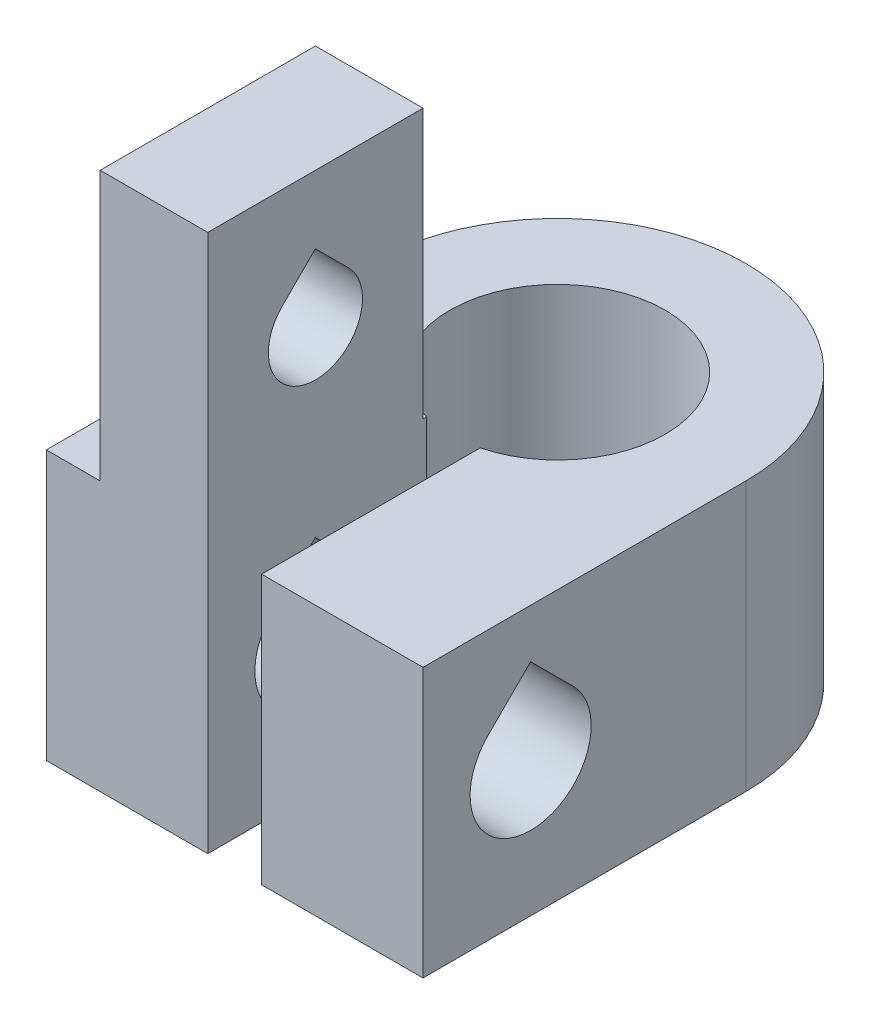
SolidWorks part; units mm, degrees
material "Printed PLA"
ref_plane "Front Plane" through (0, 0, 0) normal (0, 0, 1) x (1, 0, 0)
ref_plane "Top Plane" through (0, 0, 0) normal (0, 1, 0) x (1, 0, 0)
ref_plane "Right Plane" through (0, 0, 0) normal (1, 0, 0) x (0, 0, -1)
sketch "Sketch1" plane through (0, 0, 0) normal (0, 1, 0) x (1, 0, 0)
  line L0 (-7, -12) -> (-7, 0)
  line L1 (7, 0) -> (7, -12)
  line L2 (7, -12) -> (1, -12)
  line L3 (1, -12) -> (1, -3.873)
  line L4 (-7, -12) -> (-1, -12)
  line L5 (-1, -12) -> (-1, -3.873)
  line L6 (-1, -12) -> (1, -12) construction
  line L7 (0, -12) -> (0, 0) construction
  arc A0 (1, -3.873) -> (-1, -3.873) centre (0, 0) ccw
  arc A1 (-7, 0) -> (7, 0) centre (0, 0) cw
  dimension "D1" = 4
  dimension "D2" = 7
  dimension "D3" = 12
  dimension "D4" = 2
extrude "Boss-Extrude1" add sketch "Sketch1" along normal blind 20
sketch "Sketch2" plane through (-7, 0, 0) normal (-1, 0, 0) x (0, 0, 1)
  line L0 (6.409, 6.591) -> (8, 8.182)
  line L1 (8, 8.182) -> (9.591, 6.591)
  line L2 (8, 8.182) -> (8, 5) construction
  line L3 (0, 0) -> (12, 0) construction
  line L4 (12, 20) -> (12, 0) construction
  arc A0 (6.409, 6.591) -> (9.591, 6.591) centre (8, 5) ccw
  dimension "D1" = 4.5
  dimension "D2" = 5
  dimension "D3" = 4
extrude "Cut-Extrude1" cut sketch "Sketch2" against normal through all
sketch "Sketch3" plane through (0, 20, 0) normal (0, 1, 0) x (1, 0, 0)
  line L0 (1, -4) -> (-7, -4)
  line L1 (7, -12) -> (1, -12)
  line L2 (7, -12) -> (7, 0)
  line L3 (7, 0) -> (1, 0) construction
  line L4 (1, -12) -> (1, -4)
  line L5 (-7, 0) -> (-7, -12) construction
  line L6 (-7, -4) -> (-7, 7)
  line L7 (-7, 7) -> (7, 7)
  line L8 (7, 7) -> (7, 0)
  arc A0 (1, -3.873) -> (-1, -3.873) centre (0, 0) ccw construction
  arc A1 (7, 0) -> (-7, 0) centre (0, 0) ccw construction
extrude "Cut-Extrude2" cut sketch "Sketch3" against normal blind 10
sketch "Sketch4" plane through (-1, 0, 0) normal (1, 0, 0) x (0, 0, -1)
  line L0 (-9.2374, 16.2374) -> (-8, 17.4749)
  line L1 (-8, 17.4749) -> (-6.7626, 16.2374)
  line L2 (-8, 17.4749) -> (-8, 15) construction
  line L3 (-8, 15) -> (-8, 5) construction
  line L4 (-12, 20) -> (-4, 20) construction
  arc A0 (-9.2374, 16.2374) -> (-6.7626, 16.2374) centre (-8, 15) ccw
  dimension "D2" = 1.75
  dimension "D1" = 5
extrude "Cut-Extrude3" cut sketch "Sketch4" against normal blind 10
sketch "Sketch5" plane through (-7, 0, 0) normal (-1, 0, 0) x (0, 0, 1)
  line L1 (4, 10) -> (12, 10)
  line L2 (4, 10) -> (4, 20)
  line L3 (4, 20) -> (12, 20)
  line L4 (12, 10) -> (12, 20)
extrude "Cut-Extrude4" cut sketch "Sketch5" against normal blind 2
